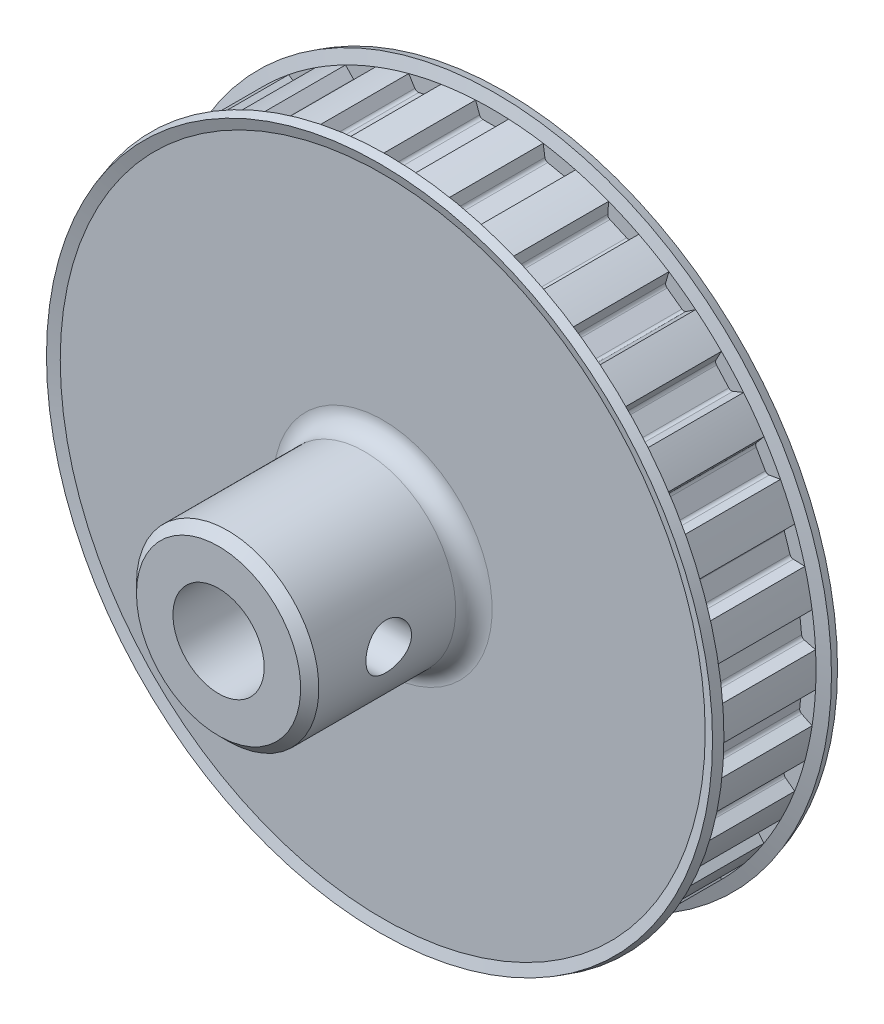
SolidWorks part; units mm, degrees
extrude "BasePulley" add sketch "Sketch1" against normal blind 13.97
sketch "Sketch1" plane through (0, 0, 0) normal (0, 0, 1) x (1, 0, 0)
  circle A0 centre (0, 0) radius 45.0977
  dimension "Outside_dia" = 90.1954
revolve "Flange" add sketch "Sketch2" angle 360 about L11
sketch "Sketch2" plane through (0, 0, 0) normal (1, 0, 0) x (0, 0, -1)
  line L0 (13.97, 45.0977) -> (14.4748, 46.7487)
  line L1 (14.4748, 46.7487) -> (15.6893, 46.3774)
  line L2 (6.985, 0) -> (6.985, 66.675) construction
  line L3 (15.6893, 46.3774) -> (15.24, 44.9079)
  line L4 (15.24, 44.9079) -> (15.24, 0)
  line L5 (0, 45.0977) -> (-0.5048, 46.7487)
  line L6 (13.97, -45.0977) -> (13.97, 45.0977) construction
  line L7 (-0.5048, 46.7487) -> (-1.7193, 46.3774)
  line L8 (-1.7193, 46.3774) -> (-1.27, 44.9079)
  line L9 (-1.27, 44.9079) -> (-1.27, 0)
  line L10 (13.97, 45.0977) -> (0, 45.0977)
  line L11 (0, 0) -> (38.2092, 0) construction
  line L12 (13.97, 0) -> (0, 0) construction
  line L13 (-1.27, 0) -> (15.24, 0)
  dimension "D1" = 6.985
  dimension "Flange_ang" = 17
  dimension "D3" = 1.27
  dimension "D2" = 45.0977
  dimension "Flange_ht" = 1.651
material "6061-T6 (SS)"
ref_plane "Plane1" through (0, 0, 0) normal (0, 0, 1) x (1, 0, 0)
ref_plane "Plane2" through (0, 0, 0) normal (0, 1, 0) x (1, 0, 0)
ref_plane "Plane3" through (0, 0, 0) normal (1, 0, 0) x (0, 0, -1)
sketch "Clipboard" plane through (0, 0, 0) normal (0, 0, 1) x (1, 0, 0)
  line L0 (0, 0) -> (14.224, 0)
  line L1 (0, 0) -> (32.9956, 19.05)
  line L2 (0, 0) -> (32.9956, -19.05)
ref_plane "Plane4" through (0, 0, -6.985) normal (0, 0, 1) x (1, 0, 0)
sketch "Sketch3" plane through (0, 0, -6.985) normal (0, 0, 1) x (1, 0, 0)
  line L0 (-2.3241, 45.0977) -> (-2.3241, 70.4977)
  line L1 (2.3241, 45.0977) -> (2.3241, 70.4977)
  line L2 (0, 0) -> (0, 45.0977) construction
  line L3 (-2.3241, 45.0977) -> (2.3241, 45.0977) construction
  line L4 (-1.275, 43.1927) -> (1.275, 43.1927)
  line L5 (2.3241, 45.0977) -> (1.7524, 43.527)
  line L6 (-2.3241, 45.0977) -> (-1.7524, 43.527)
  line L7 (2.3241, 70.4977) -> (-2.3241, 70.4977)
  arc A0 (1.275, 43.1927) -> (1.7524, 43.527) centre (1.275, 43.7007) ccw
  arc A2 (-1.7524, 43.527) -> (-1.275, 43.1927) centre (-1.275, 43.7007) ccw
  dimension "Grv_rad_bot" = 0.508
  dimension "Grv_ang" = 40
  dimension "D3" = 20
  dimension "Grv_width" = 4.6482
  dimension "D4" = 25.4
  dimension "D1" = 45.0977
  dimension "Grv_depth" = 1.905
extrude "Groove" cut sketch "Sketch3" against normal mid plane 13.97
pattern_circular "Grooves" count 30 every 12 about axis through (0, 0, -13.97) along (0, 0, 1) of "Groove"
sketch "Sketch4" plane through (0, 0, 0) normal (1, 0, 0) x (0, 0, -1)
  line L0 (0, 0) -> (47.6781, 0) construction
  line L1 (13.97, 0) -> (0, 0) construction
  line L2 (0, 0) -> (-24.13, 0)
  line L3 (-24.13, 0) -> (-24.13, 12.7)
  line L4 (-24.13, 12.7) -> (0, 12.7)
  line L5 (0, 12.7) -> (0, 0)
  line L6 (-24.13, -12.7) -> (0, -12.7) construction
revolve "BaseHub" add sketch "Sketch4" angle 360 about L0
sketch "BorSke" plane through (0, 0, 24.13) normal (0, 0, 1) x (1, 0, 0)
  circle A0 centre (0, 0) radius 6.35
extrude "Bore" cut sketch "BorSke" against normal through all
sketch "KeySke" plane through (0, 0, 24.13) normal (0, 0, 1) x (1, 0, 0)
  line L0 (1.5875, 7.874) -> (1.5875, 0)
  line L1 (1.5875, 7.874) -> (-1.5875, 7.874)
  line L2 (-1.5875, 7.874) -> (-1.5875, 0)
  line L3 (-1.5875, 0) -> (1.5875, 0)
  line L4 (0, 31.75) -> (0, -3.175) construction
extrude "Keyway" [suppressed] cut sketch "KeySke" against normal through all
pattern_circular "Keyway2" [suppressed] count 2 every 90
sketch "Sketch5" plane through (0, 0, 0) normal (1, 0, 0) x (0, 0, -1)
  line L0 (-24.13, 0) -> (-2.1351, 0) construction
  line L1 (-24.13, 12.7) -> (-24.13, -12.7) construction
  circle A0 centre (-13.1325, 0) radius 3.175
  dimension "D1" = 6.35
extrude "Cut-Extrude1" cut sketch "Sketch5" against normal through all and the other way through all
fillet "Fillet1" radius 2.54 1 edges at (-12.7, 0, 1.27)
chamfer "Chamfer1" distance 1.27 angle 45 1 edges at (12.7, 0, 24.13)
equation "\"D1@Plane4\" = \"Width@BasePulley\" / 2"
equation "\"D1@Groove\" = \"Width@BasePulley\""
equation "\"D1@Sketch3\" = \"Outside_dia@Sketch1\" / 2"
equation "\"D1@Sketch2\" = \"Width@BasePulley\" / 2"
equation "\"D2@Sketch2\" = \"Outside_dia@Sketch1\" / 2"
equation "\"D3@Sketch2\" = \"Flange_thickness@Sketch2\""
equation "\"Num_grvs@Clipboard\" = int( \"Num_grvs@Clipboard\" )"
equation "\"Show_grvs@Clipboard\" = int( \"Show_grvs@Clipboard\" )"
equation "\"Show_grvs@Clipboard\" = ((sgn( \"Show_grvs@Clipboard\" - \"Num_grvs@Clipboard\" )-1)*( \"Show_grvs@Clipboard\" - \"Num_grvs@Clipboard\" ))/-2+ \"Num_grvs@Clipboard\""
equation "\"Show_grvs@Clipboard\" = ((sgn( \"Show_grvs@Clipboard\" - 1.0)+1)*( \"Show_grvs@Clipboard\" - 1.0))/2 +1.0"
equation "\"Angle@Grooves\" = 360.0 / \"Num_grvs@Clipboard\""
equation "\"Num_grvs@Grooves\" =  \"Show_grvs@Clipboard\""
equation "\"Offset@KeySke\" = \"T_dim@Clipboard\" - \"Diameter@BorSke\" / 2.0"
equation "\"OAL@Clipboard\" = \"Overall_len@Clipboard\""
equation "\"Hub_depth@Sketch4\" = \"OAL@Clipboard\" - \"Width@BasePulley\""
